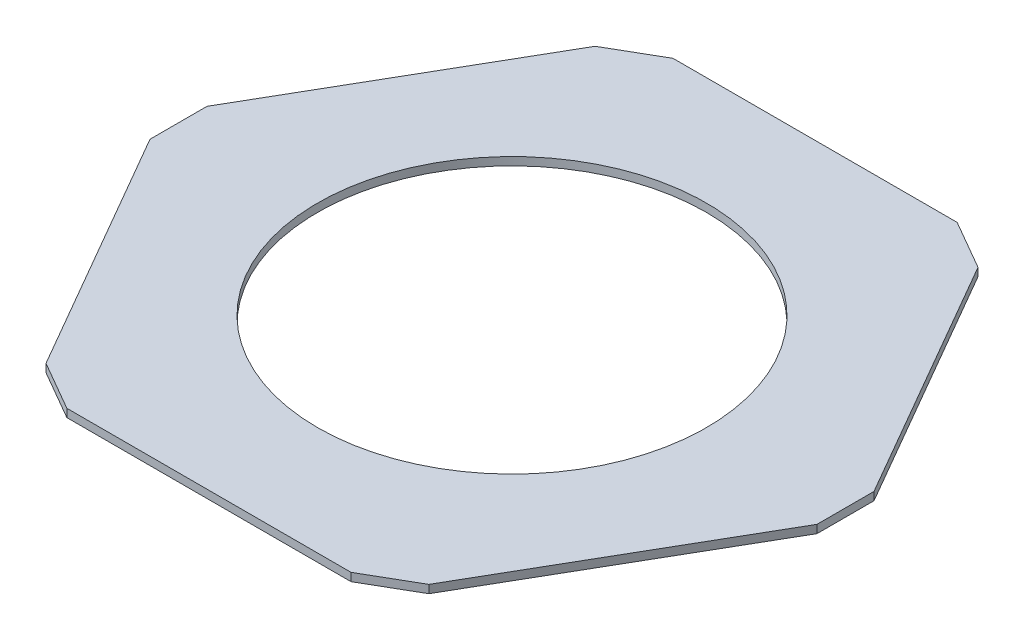
SolidWorks part; units mm, degrees
material "Ti-6Al-4VSolution treated and aged (SS)"
ref_plane "Front Plane" through (0, 0, 0) normal (0, 0, 1) x (1, 0, 0)
ref_plane "Top Plane" through (0, 0, 0) normal (0, 1, 0) x (1, 0, 0)
ref_plane "Right Plane" through (0, 0, 0) normal (1, 0, 0) x (0, 0, -1)
sketch "Sketch1" plane through (0, 0, 0) normal (0, 1, 0) x (1, 0, 0)
  line L0 (438.3179, 934.9709) -> (590.5496, 847.0799)
  line L1 (1028.8675, 87.891) -> (590.5496, 847.0799)
  line L2 (438.3179, 934.9709) -> (-438.3179, 934.9709)
  line L3 (-590.5496, 847.0799) -> (-1028.8675, 87.891)
  line L4 (-1028.8675, -87.891) -> (-590.5496, -847.0799)
  line L5 (-438.3179, -934.9709) -> (438.3179, -934.9709)
  line L6 (590.5496, -847.0799) -> (1028.8675, -87.891)
  line L7 (1028.8675, 87.891) -> (1028.8675, -87.891)
  line L8 (590.5496, -847.0799) -> (438.3179, -934.9709)
  line L9 (-438.3179, -934.9709) -> (-590.5496, -847.0799)
  line L10 (-1028.8675, -87.891) -> (-1028.8675, 87.891)
  line L11 (-590.5496, 847.0799) -> (-438.3179, 934.9709)
  point P12 (0, 0)
  dimension "D1" = 30
  dimension "D2" = 2057.735
  dimension "D3" = 876.6359
extrude "Boss-Extrude1" add sketch "Sketch1" along normal blind 25
sketch "Sketch2" plane through (0, 25, 0) normal (0, 1, 0) x (1, 0, 0)
  circle A0 centre (0, 0) radius 600
  dimension "D1" = 1200
extrude "Cut-Extrude1" cut sketch "Sketch2" against normal up to next
